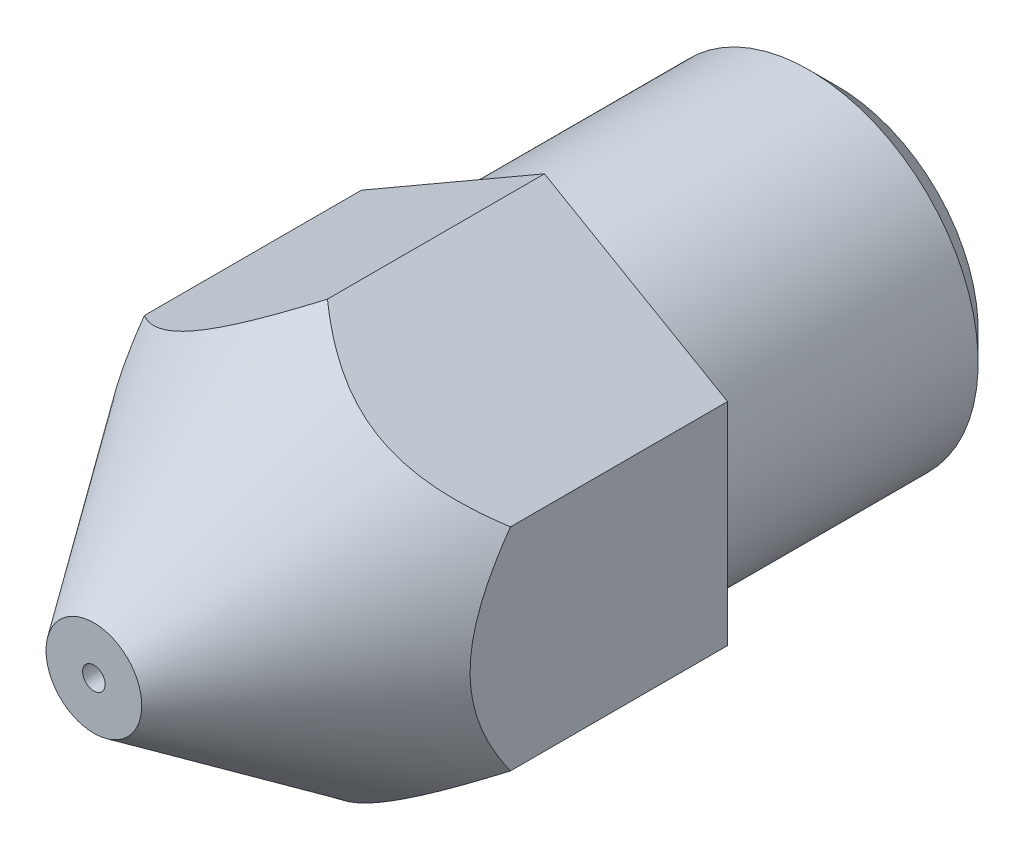
SolidWorks part; units mm, degrees
ref_plane "Front Plane" through (0, 0, 0) normal (0, 0, 1) x (1, 0, 0)
ref_plane "Top Plane" through (0, 0, 0) normal (0, 1, 0) x (1, 0, 0)
ref_plane "Right Plane" through (0, 0, 0) normal (1, 0, 0) x (0, 0, -1)
sketch "Sketch1" plane through (0, 0, 0) normal (0, 1, 0) x (1, 0, 0)
  line L0 (0, 0) -> (0, -50000) construction
  line L1 (0, 0) -> (-50000, 0) construction
  line L2 (1, 8.7) -> (3, 8.7)
  line L3 (0.85, -4.5) -> (4, 0)
  line L4 (4, 0) -> (4, 3.5)
  line L5 (0, -4.5) -> (0, -3.6732)
  line L10 (1, 8.7) -> (1, -1.9412)
  line L14 (3, 8.7) -> (3, 3.5)
  line L20 (0, -3.6732) -> (1, -1.9412)
  line L23 (3, 3.5) -> (4, 3.5)
  line L24 (0, -4.5) -> (0.85, -4.5)
  line L25 (4, 0) -> (50001.5, 0) construction
  dimension "D1" = 1
  dimension "D2" = 3
  dimension "D3" = 3.5
  dimension "D4" = 1.7
  dimension "D5" = 0.8268
  dimension "D6" = 13.2
  dimension "D7" = 5.2
  dimension "D9" = 4
  dimension "D11" = 30
ref_axis "Axis1" through (0, 0, 0) along (0, 0, 1)
revolve "Revolve1" add sketch "Sketch1" angle 360 about axis through (0, 0, 0) along (0, 0, 1)
cosmetic thread "Cosmetic Thread1" parameters "D2"=4.891
sketch "Sketch2" plane through (0, 0, -3.5) normal (0, 0, -1) x (-1, 0, 0)
  line L0 (0, 0) -> (0, 50000) construction
  line L1 (0, 0) -> (50000, 0) construction
  line L2 (3.25, 1.8764) -> (0, 3.7528)
  line L3 (3.25, 1.8764) -> (3.25, -1.8764)
  line L4 (3.25, -1.8764) -> (0, -3.7528)
  line L5 (0, 0) -> (43301.2702, 25000) construction
  line L6 (0, 0) -> (43062.4912, -24862.1409) construction
  line L7 (-3.25, 1.8764) -> (0, 3.7528)
  line L8 (-3.25, 1.8764) -> (-3.25, -1.8764)
  line L9 (-3.25, -1.8764) -> (0, -3.7528)
  dimension "D1" = 60
  dimension "D2" = 30
  dimension "D3" = 3.25
extrude "Cut-Extrude2" cut sketch "Sketch2" against normal blind 10 flip side to cut
chamfer "Chamfer1" distance 0.5 angle 45 1 edges at (-3, 0, -8.7)
sketch "Sketch3" plane through (0, 0, 4.5) normal (0, 0, 1) x (1, 0, 0)
  circle A0 centre (0, 0) radius 0.2
  dimension "D1" = 0.4
extrude "Cut-Extrude3" cut sketch "Sketch3" against normal through all
